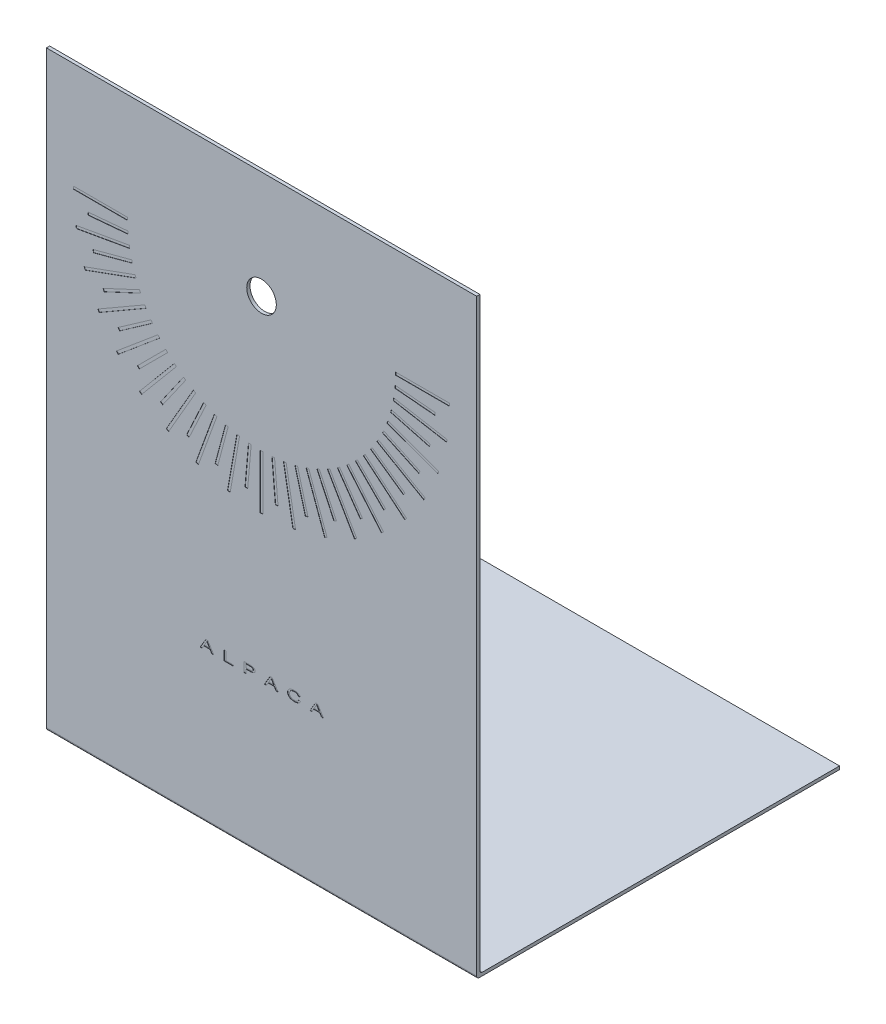
SolidWorks part; units mm, degrees
ref_plane "Front Plane" through (0, 0, 0) normal (0, 0, 1) x (1, 0, 0)
ref_plane "Top Plane" through (0, 0, 0) normal (0, 1, 0) x (1, 0, 0)
ref_plane "Right Plane" through (0, 0, 0) normal (1, 0, 0) x (0, 0, -1)
sketch "Sketch1" plane through (0, 0, 0) normal (1, 0, 0) x (0, 0, -1)
  line L2 (0, 0) -> (0, 220)
  line L3 (0, 220) -> (1.2, 220)
  line L4 (1.2, 1.2) -> (1.2, 220)
  line L5 (0, 0) -> (135, 0)
  line L7 (1.2, 1.2) -> (135, 1.2)
  line L8 (135, 0) -> (135, 1.2)
  dimension "D1" = 1.2
  dimension "D2" = 1.2
  dimension "D3" = 220
  dimension "D4" = 135
extrude "Boss-Extrude1" add sketch "Sketch1" along normal mid plane 160
fillet "Fillet1" radius 1 2 edges at (0, 1.2, -1.2) (0, 0, 0)
sketch "Sketch2" plane through (0, 0, -1.2) normal (0, 0, -1) x (-1, 0, 0)
  line L0 (-80, 2.2) -> (-80, 220) construction
  line L1 (-80, 220) -> (80, 220) construction
  circle A0 centre (0, 180) radius 5.5
  dimension "D3" = 11
  dimension "D1" = 80
  dimension "D2" = 40
extrude "Cut-Extrude1" cut sketch "Sketch2" against normal through all
sketch "Sketch3" plane through (0, 0, 0) normal (0, 0, 1) x (1, 0, 0)
  line L0 (-70, 180) -> (-50, 180) construction
  line L1 (-50, 180.5) -> (-70, 180.5)
  line L2 (-50, 180.5) -> (-50, 179.5)
  line L3 (-50, 179.5) -> (-70, 179.5)
  line L4 (-70, 180.5) -> (-70, 179.5)
  line L5 (0, 180) -> (-80, 180) construction
  line L6 (-80, 220) -> (-80, 1) construction
  dimension "D1" = 1
  dimension "D2" = 20
  dimension "D3" = 50
extrude "Cut-Extrude2" cut sketch "Sketch3" against normal blind 0.1
pattern_circular "CirPattern1" count 19 every 10 about axis through (0, 180, 0) along (0, 0, 1) of "Cut-Extrude2"
sketch "Sketch5" plane through (0, 0, 0) normal (0, 0, 1) x (1, 0, 0)
  line L0 (0, 180) -> (-80, 180) construction
  line L1 (-80, 220) -> (-80, 1) construction
  line L2 (-50, 180.5) -> (-70, 180.5) construction
  line L3 (-49.8648, 179.5) -> (-64.7868, 179.5)
  line L4 (-49.8648, 179.5) -> (-49.8648, 180.5)
  line L5 (-49.8648, 180.5) -> (-64.7868, 180.5)
  line L6 (-64.7868, 179.5) -> (-64.7868, 180.5)
  line L7 (-49.8648, 179.5) -> (-64.7868, 180.5) construction
  line L8 (-49.8648, 180.5) -> (-64.7868, 179.5) construction
  point P5 (-57.3258, 180)
extrude "Cut-Extrude3" cut sketch "Sketch5" against normal blind 0.1
pattern_circular "CirPattern2" count 37 every 5 about axis through (0, 180, 0) along (0, 0, 1) of "Cut-Extrude3"
sketch "Sketch6" plane through (0, 0, 0) normal (0, 0, 1) x (1, 0, 0)
  line L0 (0, 180) -> (0, 1) construction
  line L1 (-80, 1) -> (80, 1) construction
  line L2 (-22.8303, 55.5794) -> (22.8303, 55.5794) construction
  text T0 "ALPACA" font "Arial" height 3.5
  point P11 (0, 55.5794)
extrude "Cut-Extrude4" cut sketch "Sketch6" against normal blind 0.1
